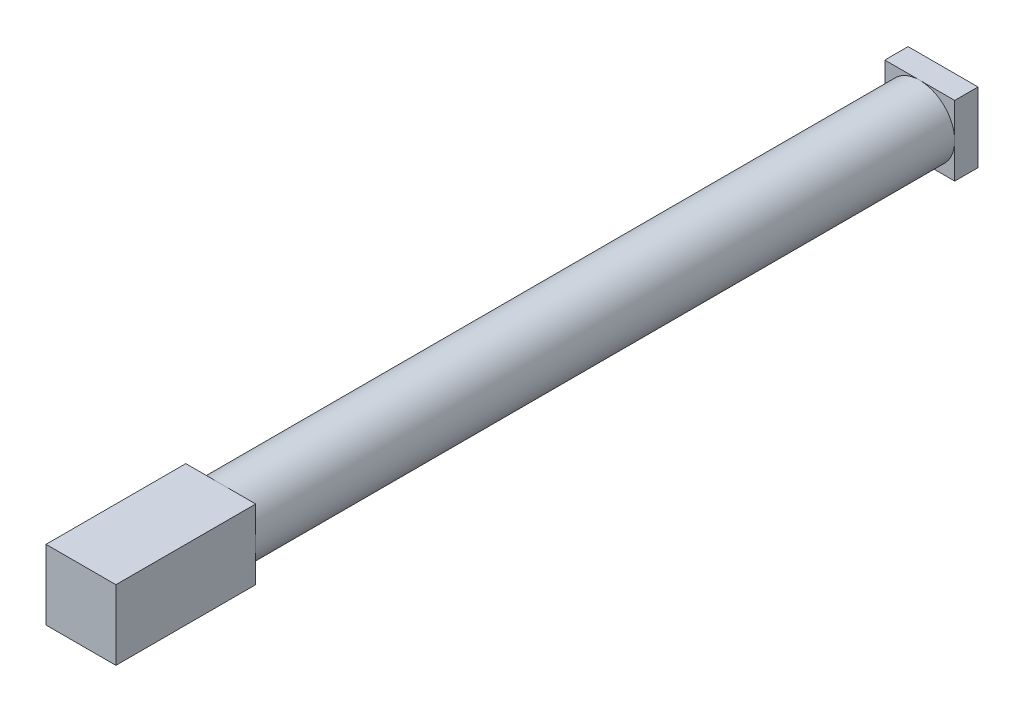
SolidWorks part; units mm, degrees
material "1023 Carbon Steel Sheet (SS)"
ref_plane "Front Plane" through (0, 0, 0) normal (0, 0, 1) x (1, 0, 0)
ref_plane "Top Plane" through (0, 0, 0) normal (0, 1, 0) x (1, 0, 0)
ref_plane "Right Plane" through (0, 0, 0) normal (1, 0, 0) x (0, 0, -1)
sketch "Sketch1" plane through (0, 0, 0) normal (0, 0, 1) x (1, 0, 0)
  circle A0 centre (0, 0) radius 1.905
  dimension "D1" = 3.81
extrude "Boss-Extrude1" add sketch "Sketch1" along normal mid plane 38.1
sketch "Sketch2" plane through (0, 0, 19.05) normal (0, 0, 1) x (1, 0, 0)
  line L1 (-1.905, -1.905) -> (1.905, -1.905)
  line L2 (-1.905, -1.905) -> (-1.905, 1.905)
  line L3 (-1.905, 1.905) -> (1.905, 1.905)
  line L4 (1.905, -1.905) -> (1.905, 1.905)
  line L5 (-1.905, -1.905) -> (1.905, 1.905) construction
  line L6 (-1.905, 1.905) -> (1.905, -1.905) construction
  point P0 (0, 0)
  dimension "D1" = 3.81
extrude "Boss-Extrude2" add sketch "Sketch2" along normal blind 7.62
sketch "Sketch3" plane through (0, 0, -19.05) normal (0, 0, -1) x (-1, 0, 0)
  line L1 (-1.905, 1.905) -> (1.905, 1.905)
  line L2 (-1.905, 1.905) -> (-1.905, -1.905)
  line L3 (-1.905, -1.905) -> (1.905, -1.905)
  line L4 (1.905, 1.905) -> (1.905, -1.905)
  line L5 (-1.905, 1.905) -> (1.905, -1.905) construction
  line L6 (-1.905, -1.905) -> (1.905, 1.905) construction
  point P0 (0, 0)
  dimension "D1" = 3.81
extrude "Boss-Extrude3" add sketch "Sketch3" along normal blind 1.27
